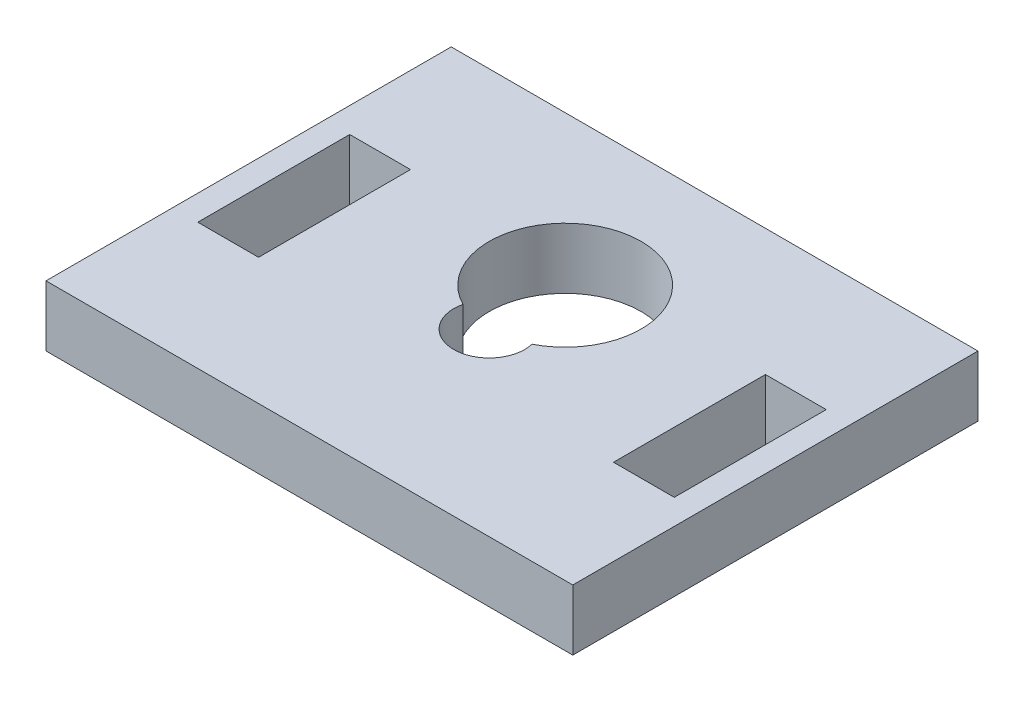
SolidWorks part; units mm, degrees
material "6061-T6 (SS)"
ref_plane "Alzado" through (0, 0, 0) normal (0, 0, 1) x (1, 0, 0)
ref_plane "Planta" through (0, 0, 0) normal (0, 1, 0) x (1, 0, 0)
ref_plane "Vista lateral" through (0, 0, 0) normal (1, 0, 0) x (0, 0, -1)
sketch "Croquis1" plane through (0, 0, 0) normal (0, 1, 0) x (1, 0, 0)
  line L1 (-26, -20) -> (26, -20)
  line L2 (-26, -20) -> (-26, 20)
  line L3 (-26, 20) -> (26, 20)
  line L4 (26, -20) -> (26, 20)
  line L5 (-26, -20) -> (26, 20) construction
  line L6 (-26, 20) -> (26, -20) construction
  point P0 (0, 0)
  dimension "D1" = 40
  dimension "D2" = 52
extrude "Saliente-Extruir1" add sketch "Croquis1" along normal mid plane 6
sketch "Croquis2" plane through (0, 3, 0) normal (0, 1, 0) x (1, 0, 0)
  line L1 (-23.5187, 7.5) -> (-17.5187, 7.5)
  line L2 (-23.5187, 7.5) -> (-23.5187, -7.5)
  line L3 (-23.5187, -7.5) -> (-17.5187, -7.5)
  line L4 (-17.5187, 7.5) -> (-17.5187, -7.5)
  line L5 (17.5187, 7.5) -> (23.5187, 7.5)
  line L6 (17.5187, 7.5) -> (17.5187, -7.5)
  line L7 (17.5187, -7.5) -> (23.5187, -7.5)
  line L8 (23.5187, 7.5) -> (23.5187, -7.5)
extrude "Cortar-Extruir1" cut sketch "Croquis2" against normal through all
sketch "Croquis3" plane through (0, 3, 0) normal (0, 1, 0) x (1, 0, 0)
  arc A0 (3.4034, -1.4333) -> (-3.4034, -1.4333) centre (0, 5.25) ccw
  arc A1 (2.5, -0.4782) -> (-2.5, -0.4782) centre (0, 5.25) ccw construction
  arc A2 (-3.4034, -1.4333) -> (3.4034, -1.4333) centre (0, -2.25) ccw
  dimension "D1" = 15
  dimension "D2" = 7
extrude "Cortar-Extruir2" cut sketch "Croquis3" against normal through all
